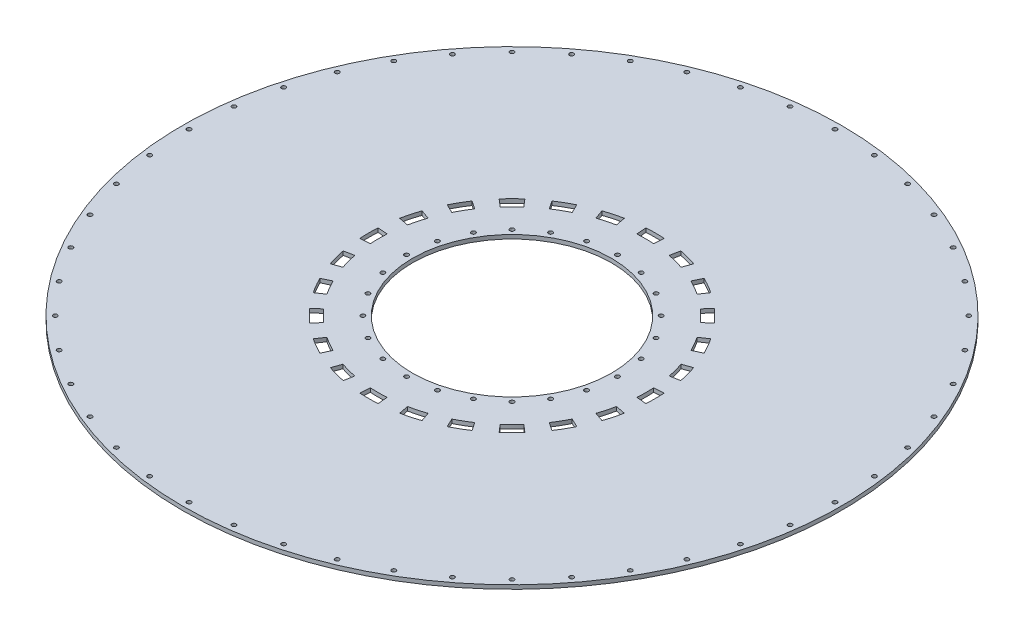
SolidWorks part; units mm, degrees
ref_plane "Front Plane" through (0, 0, 0) normal (0, 0, 1) x (1, 0, 0)
ref_plane "Top Plane" through (0, 0, 0) normal (0, 1, 0) x (1, 0, 0)
ref_plane "Right Plane" through (0, 0, 0) normal (1, 0, 0) x (0, 0, -1)
sketch "Sketch2" plane through (0, 0, 0) normal (0, 1, 0) x (1, 0, 0)
  line L0 (0, 0) -> (0, 231.6511) construction
  line L1 (-8.25, 109.6902) -> (-7.5, 99.7184) construction
  line L2 (8.25, 109.6902) -> (7.5, 99.7184) construction
  line L3 (-6.9092, 108.5303) -> (-6.3467, 101.0509)
  line L4 (6.9092, 108.5303) -> (6.3467, 101.0509)
  line L5 (21.4159, 106.6205) -> (20.0235, 99.2503)
  line L6 (34.7635, 103.044) -> (32.2843, 95.965)
  line L7 (48.2816, 97.4446) -> (45.029, 90.686)
  line L8 (60.2487, 90.5354) -> (56.0218, 84.3393)
  line L9 (71.8569, 81.6281) -> (66.966, 75.9416)
  line L10 (81.6281, 71.8569) -> (75.9416, 66.966)
  line L11 (90.5354, 60.2487) -> (84.3393, 56.0218)
  line L12 (97.4446, 48.2816) -> (90.686, 45.029)
  line L13 (103.044, 34.7635) -> (95.965, 32.2843)
  line L14 (106.6205, 21.4159) -> (99.2503, 20.0235)
  line L15 (108.5303, 6.9092) -> (101.0509, 6.3467)
  line L16 (108.5303, -6.9092) -> (101.0509, -6.3467)
  line L17 (106.6205, -21.4159) -> (99.2503, -20.0235)
  line L18 (103.044, -34.7635) -> (95.965, -32.2843)
  line L19 (97.4446, -48.2816) -> (90.686, -45.029)
  line L20 (90.5354, -60.2487) -> (84.3393, -56.0218)
  line L21 (81.6281, -71.8569) -> (75.9416, -66.966)
  line L22 (71.8569, -81.6281) -> (66.966, -75.9416)
  line L23 (60.2487, -90.5354) -> (56.0218, -84.3393)
  line L24 (48.2816, -97.4446) -> (45.029, -90.686)
  line L25 (34.7635, -103.044) -> (32.2843, -95.965)
  line L26 (21.4159, -106.6205) -> (20.0235, -99.2503)
  line L27 (6.9092, -108.5303) -> (6.3467, -101.0509)
  line L28 (-6.9092, -108.5303) -> (-6.3467, -101.0509)
  line L29 (-21.4159, -106.6205) -> (-20.0235, -99.2503)
  line L30 (-34.7635, -103.044) -> (-32.2843, -95.965)
  line L31 (-48.2816, -97.4446) -> (-45.029, -90.686)
  line L32 (-60.2487, -90.5354) -> (-56.0218, -84.3393)
  line L33 (-71.8569, -81.6281) -> (-66.966, -75.9416)
  line L34 (-81.6281, -71.8569) -> (-75.9416, -66.966)
  line L35 (-90.5354, -60.2487) -> (-84.3393, -56.0218)
  line L36 (-97.4446, -48.2816) -> (-90.686, -45.029)
  line L37 (-103.044, -34.7635) -> (-95.965, -32.2843)
  line L38 (-106.6205, -21.4159) -> (-99.2503, -20.0235)
  line L39 (-108.5303, -6.9092) -> (-101.0509, -6.3467)
  line L40 (-108.5303, 6.9092) -> (-101.0509, 6.3467)
  line L41 (-106.6205, 21.4159) -> (-99.2503, 20.0235)
  line L42 (-103.044, 34.7635) -> (-95.965, 32.2843)
  line L43 (-97.4446, 48.2816) -> (-90.686, 45.029)
  line L44 (-90.5354, 60.2487) -> (-84.3393, 56.0218)
  line L45 (-81.6281, 71.8569) -> (-75.9416, 66.966)
  line L46 (-71.8569, 81.6281) -> (-66.966, 75.9416)
  line L47 (-60.2487, 90.5354) -> (-56.0218, 84.3393)
  line L48 (-48.2816, 97.4446) -> (-45.029, 90.686)
  line L49 (-34.7635, 103.044) -> (-32.2843, 95.965)
  line L50 (-21.4159, 106.6205) -> (-20.0235, 99.2503)
  circle A0 centre (0, 0) radius 250
  circle A1 centre (0, 0) radius 145 construction
  arc A2 (8.25, 109.6902) -> (-8.25, 109.6902) centre (0, 0) ccw construction
  arc A3 (7.5, 99.7184) -> (-7.5, 99.7184) centre (0, 0) ccw construction
  circle A4 centre (0, 0) radius 95 construction
  arc A5 (-7.5, 99.7184) -> (7.5, 99.7184) centre (0, 0) ccw construction
  arc A6 (-8.25, 109.6902) -> (8.25, 109.6902) centre (0, 0) ccw construction
  arc A7 (6.3467, 101.0509) -> (-6.3467, 101.0509) centre (0, 0) ccw
  arc A8 (6.9092, 108.5303) -> (-6.9092, 108.5303) centre (0, 0) ccw
  arc A9 (32.2843, 95.965) -> (20.0235, 99.2503) centre (0, 0) ccw
  arc A10 (34.7635, 103.044) -> (21.4159, 106.6205) centre (0, 0) ccw
  arc A11 (56.0218, 84.3393) -> (45.029, 90.686) centre (0, 0) ccw
  arc A12 (60.2487, 90.5354) -> (48.2816, 97.4446) centre (0, 0) ccw
  arc A13 (75.9416, 66.966) -> (66.966, 75.9416) centre (0, 0) ccw
  arc A14 (81.6281, 71.8569) -> (71.8569, 81.6281) centre (0, 0) ccw
  arc A15 (90.686, 45.029) -> (84.3393, 56.0218) centre (0, 0) ccw
  arc A16 (97.4446, 48.2816) -> (90.5354, 60.2487) centre (0, 0) ccw
  arc A17 (99.2503, 20.0235) -> (95.965, 32.2843) centre (0, 0) ccw
  arc A18 (106.6205, 21.4159) -> (103.044, 34.7635) centre (0, 0) ccw
  arc A19 (101.0509, -6.3467) -> (101.0509, 6.3467) centre (0, 0) ccw
  arc A20 (108.5303, -6.9092) -> (108.5303, 6.9092) centre (0, 0) ccw
  arc A21 (95.965, -32.2843) -> (99.2503, -20.0235) centre (0, 0) ccw
  arc A22 (103.044, -34.7635) -> (106.6205, -21.4159) centre (0, 0) ccw
  circle A23 centre (0, 245) radius 1.6
  circle A31 centre (0, 0) radius 75.5
  circle A32 centre (0, 80) radius 1.6
  circle A33 centre (0, 40) radius 1.6 construction
  circle A34 centre (10.3528, 38.637) radius 1.6 construction
  circle A35 centre (20.7055, 77.2741) radius 1.6
  circle A36 centre (20, 34.641) radius 1.6 construction
  circle A37 centre (40, 69.282) radius 1.6
  circle A38 centre (28.2843, 28.2843) radius 1.6 construction
  circle A39 centre (56.5685, 56.5685) radius 1.6
  circle A40 centre (34.641, 20) radius 1.6 construction
  circle A41 centre (69.282, 40) radius 1.6
  circle A42 centre (38.637, 10.3528) radius 1.6 construction
  circle A43 centre (77.2741, 20.7055) radius 1.6
  circle A44 centre (40, 0) radius 1.6 construction
  circle A45 centre (80, 0) radius 1.6
  circle A46 centre (38.637, -10.3528) radius 1.6 construction
  circle A47 centre (77.2741, -20.7055) radius 1.6
  circle A48 centre (236.6518, -63.4107) radius 1.6 [skipped]
  circle A49 centre (63.4107, 236.6518) radius 1.6 [skipped]
  circle A50 centre (122.5, 212.1762) radius 1.6 [skipped]
  circle A51 centre (245, 0) radius 1.6 [skipped]
  circle A52 centre (236.6518, 63.4107) radius 1.6 [skipped]
  circle A53 centre (173.2412, 173.2412) radius 1.6 [skipped]
  circle A54 centre (212.1762, 122.5) radius 1.6 [skipped]
  circle A55 centre (31.9789, 242.904) radius 1.6
  circle A56 centre (63.4107, 236.6518) radius 1.6
  circle A57 centre (93.7574, 226.3505) radius 1.6
  circle A58 centre (122.5, 212.1762) radius 1.6
  circle A59 centre (149.1466, 194.3716) radius 1.6
  arc A60 (84.3393, -56.0218) -> (90.686, -45.029) centre (0, 0) ccw
  arc A61 (90.5354, -60.2487) -> (97.4446, -48.2816) centre (0, 0) ccw
  circle A62 centre (212.1762, -122.5) radius 1.6
  circle A63 centre (34.641, -20) radius 1.6 construction
  circle A64 centre (69.282, -40) radius 1.6
  arc A65 (66.966, -75.9416) -> (75.9416, -66.966) centre (0, 0) ccw
  arc A66 (71.8569, -81.6281) -> (81.6281, -71.8569) centre (0, 0) ccw
  circle A67 centre (173.2412, -173.2412) radius 1.6
  circle A68 centre (28.2843, -28.2843) radius 1.6 construction
  circle A69 centre (56.5685, -56.5685) radius 1.6
  arc A70 (45.029, -90.686) -> (56.0218, -84.3393) centre (0, 0) ccw
  arc A71 (48.2816, -97.4446) -> (60.2487, -90.5354) centre (0, 0) ccw
  circle A72 centre (122.5, -212.1762) radius 1.6
  circle A73 centre (20, -34.641) radius 1.6 construction
  circle A74 centre (40, -69.282) radius 1.6
  arc A75 (20.0235, -99.2503) -> (32.2843, -95.965) centre (0, 0) ccw
  arc A76 (21.4159, -106.6205) -> (34.7635, -103.044) centre (0, 0) ccw
  circle A77 centre (63.4107, -236.6518) radius 1.6
  circle A78 centre (10.3528, -38.637) radius 1.6 construction
  circle A79 centre (20.7055, -77.2741) radius 1.6
  arc A80 (-6.3467, -101.0509) -> (6.3467, -101.0509) centre (0, 0) ccw
  arc A81 (-6.9092, -108.5303) -> (6.9092, -108.5303) centre (0, 0) ccw
  circle A82 centre (0, -245) radius 1.6
  circle A83 centre (0, -40) radius 1.6 construction
  circle A84 centre (0, -80) radius 1.6
  arc A85 (-32.2843, -95.965) -> (-20.0235, -99.2503) centre (0, 0) ccw
  arc A86 (-34.7635, -103.044) -> (-21.4159, -106.6205) centre (0, 0) ccw
  circle A87 centre (-63.4107, -236.6518) radius 1.6
  circle A88 centre (-10.3528, -38.637) radius 1.6 construction
  circle A89 centre (-20.7055, -77.2741) radius 1.6
  arc A90 (-56.0218, -84.3393) -> (-45.029, -90.686) centre (0, 0) ccw
  arc A91 (-60.2487, -90.5354) -> (-48.2816, -97.4446) centre (0, 0) ccw
  circle A92 centre (-122.5, -212.1762) radius 1.6
  circle A93 centre (-20, -34.641) radius 1.6 construction
  circle A94 centre (-40, -69.282) radius 1.6
  arc A95 (-75.9416, -66.966) -> (-66.966, -75.9416) centre (0, 0) ccw
  arc A96 (-81.6281, -71.8569) -> (-71.8569, -81.6281) centre (0, 0) ccw
  circle A97 centre (-173.2412, -173.2412) radius 1.6
  circle A98 centre (-28.2843, -28.2843) radius 1.6 construction
  circle A99 centre (-56.5685, -56.5685) radius 1.6
  arc A100 (-90.686, -45.029) -> (-84.3393, -56.0218) centre (0, 0) ccw
  arc A101 (-97.4446, -48.2816) -> (-90.5354, -60.2487) centre (0, 0) ccw
  circle A102 centre (-212.1762, -122.5) radius 1.6
  circle A103 centre (-34.641, -20) radius 1.6 construction
  circle A104 centre (-69.282, -40) radius 1.6
  arc A105 (-99.2503, -20.0235) -> (-95.965, -32.2843) centre (0, 0) ccw
  arc A106 (-106.6205, -21.4159) -> (-103.044, -34.7635) centre (0, 0) ccw
  circle A107 centre (-236.6518, -63.4107) radius 1.6
  circle A108 centre (-38.637, -10.3528) radius 1.6 construction
  circle A109 centre (-77.2741, -20.7055) radius 1.6
  arc A110 (-101.0509, 6.3467) -> (-101.0509, -6.3467) centre (0, 0) ccw
  arc A111 (-108.5303, 6.9092) -> (-108.5303, -6.9092) centre (0, 0) ccw
  circle A112 centre (-245, 0) radius 1.6
  circle A113 centre (-40, 0) radius 1.6 construction
  circle A114 centre (-80, 0) radius 1.6
  arc A115 (-95.965, 32.2843) -> (-99.2503, 20.0235) centre (0, 0) ccw
  arc A116 (-103.044, 34.7635) -> (-106.6205, 21.4159) centre (0, 0) ccw
  circle A117 centre (-236.6518, 63.4107) radius 1.6
  circle A118 centre (-38.637, 10.3528) radius 1.6 construction
  circle A119 centre (-77.2741, 20.7055) radius 1.6
  arc A120 (-84.3393, 56.0218) -> (-90.686, 45.029) centre (0, 0) ccw
  arc A121 (-90.5354, 60.2487) -> (-97.4446, 48.2816) centre (0, 0) ccw
  circle A122 centre (-212.1762, 122.5) radius 1.6
  circle A123 centre (-34.641, 20) radius 1.6 construction
  circle A124 centre (-69.282, 40) radius 1.6
  arc A125 (-66.966, 75.9416) -> (-75.9416, 66.966) centre (0, 0) ccw
  arc A126 (-71.8569, 81.6281) -> (-81.6281, 71.8569) centre (0, 0) ccw
  circle A127 centre (-173.2412, 173.2412) radius 1.6
  circle A128 centre (-28.2843, 28.2843) radius 1.6 construction
  circle A129 centre (-56.5685, 56.5685) radius 1.6
  arc A130 (-45.029, 90.686) -> (-56.0218, 84.3393) centre (0, 0) ccw
  arc A131 (-48.2816, 97.4446) -> (-60.2487, 90.5354) centre (0, 0) ccw
  circle A132 centre (-122.5, 212.1762) radius 1.6
  circle A133 centre (-20, 34.641) radius 1.6 construction
  circle A134 centre (-40, 69.282) radius 1.6
  arc A135 (-20.0235, 99.2503) -> (-32.2843, 95.965) centre (0, 0) ccw
  arc A136 (-21.4159, 106.6205) -> (-34.7635, 103.044) centre (0, 0) ccw
  circle A137 centre (-63.4107, 236.6518) radius 1.6
  circle A138 centre (-10.3528, 38.637) radius 1.6 construction
  circle A139 centre (-20.7055, 77.2741) radius 1.6
  circle A140 centre (173.2412, 173.2412) radius 1.6
  circle A141 centre (194.3716, 149.1466) radius 1.6
  circle A142 centre (212.1762, 122.5) radius 1.6
  circle A143 centre (226.3505, 93.7574) radius 1.6
  circle A144 centre (236.6518, 63.4107) radius 1.6
  circle A145 centre (242.904, 31.9789) radius 1.6
  circle A146 centre (245, 0) radius 1.6
  circle A147 centre (242.904, -31.9789) radius 1.6
  circle A148 centre (236.6518, -63.4107) radius 1.6
  circle A149 centre (226.3505, -93.7574) radius 1.6
  circle A150 centre (212.1762, -122.5) radius 1.6
  circle A151 centre (194.3716, -149.1466) radius 1.6
  circle A152 centre (173.2412, -173.2412) radius 1.6
  circle A153 centre (149.1466, -194.3716) radius 1.6
  circle A154 centre (122.5, -212.1762) radius 1.6
  circle A155 centre (93.7574, -226.3505) radius 1.6
  circle A156 centre (63.4107, -236.6518) radius 1.6
  circle A157 centre (31.9789, -242.904) radius 1.6
  circle A158 centre (0, -245) radius 1.6
  circle A159 centre (-31.9789, -242.904) radius 1.6
  circle A160 centre (-63.4107, -236.6518) radius 1.6
  circle A161 centre (-93.7574, -226.3505) radius 1.6
  circle A162 centre (-122.5, -212.1762) radius 1.6
  circle A163 centre (-149.1466, -194.3716) radius 1.6
  circle A164 centre (-173.2412, -173.2412) radius 1.6
  circle A165 centre (-194.3716, -149.1466) radius 1.6
  circle A166 centre (-212.1762, -122.5) radius 1.6
  circle A167 centre (-226.3505, -93.7574) radius 1.6
  circle A168 centre (-236.6518, -63.4107) radius 1.6
  circle A169 centre (-242.904, -31.9789) radius 1.6
  circle A170 centre (-245, 0) radius 1.6
  circle A171 centre (-242.904, 31.9789) radius 1.6
  circle A172 centre (-236.6518, 63.4107) radius 1.6
  circle A173 centre (-226.3505, 93.7574) radius 1.6
  circle A174 centre (-212.1762, 122.5) radius 1.6
  circle A175 centre (-194.3716, 149.1466) radius 1.6
  circle A176 centre (-173.2412, 173.2412) radius 1.6
  circle A177 centre (-149.1466, 194.3716) radius 1.6
  circle A178 centre (-122.5, 212.1762) radius 1.6
  circle A179 centre (-93.7574, 226.3505) radius 1.6
  circle A180 centre (-63.4107, 236.6518) radius 1.6
  circle A181 centre (-31.9789, 242.904) radius 1.6
  point P46 (0, 0)
  point P62 (0, 0)
  dimension "D1" = 500
  dimension "D2" = 290
  dimension "D3" = 220
  dimension "D4" = 200
  dimension "D5" = 190
  dimension "D9" = 3.2
  dimension "D11" = 151
  dimension "D12" = 40
  dimension "D14" = 3.2
  dimension "D6" = 15
  dimension "D7" = 1.25
  dimension "D10" = 245
  dimension "D13" = 40
  dimension "D15" = 48
  dimension "D8" = 24
extrude "Boss-Extrude1" add sketch "Sketch2" along normal mid plane 3 contours A0 A137 A136 L50 A135 L49 A132 A131 L48 A130 L47 A127 A126 L46 A125 L45 A121 L44 A120 L43 A117 A116 L42 A115 L41 A112 A111 L40 A110 L39 A107 A106 L38 A105 L37 A101 L36
